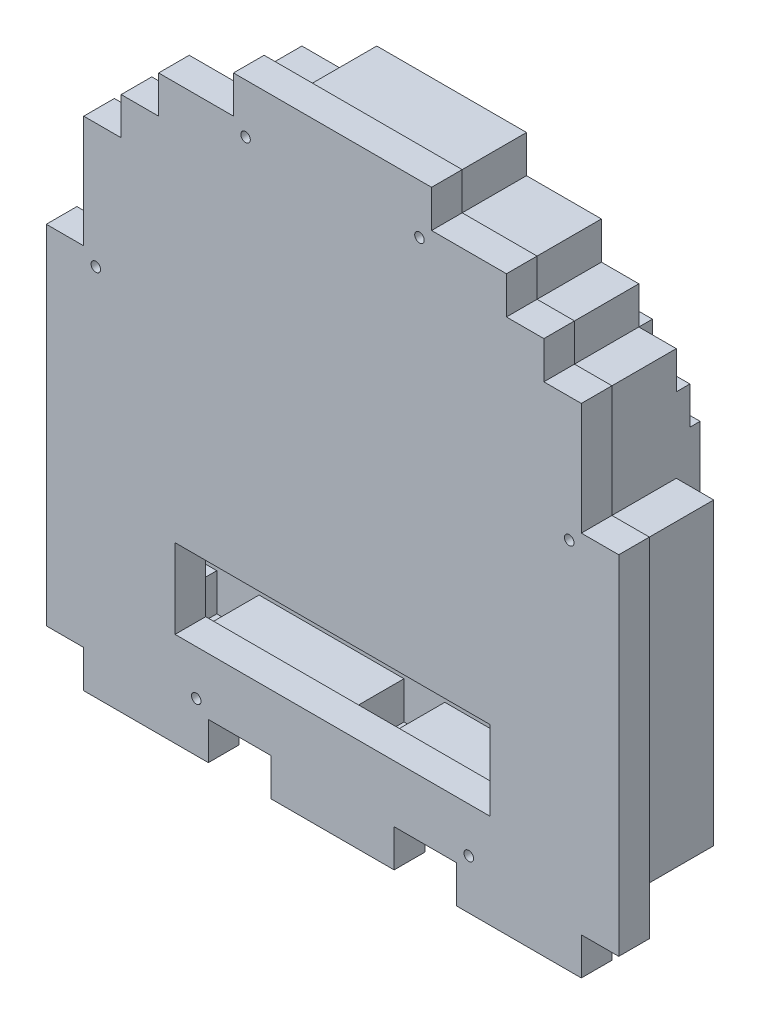
SolidWorks part; units mm, degrees
ref_plane "Alzado" through (0, 0, 0) normal (0, 0, 1) x (1, 0, 0)
ref_plane "Planta" through (0, 0, 0) normal (0, 1, 0) x (1, 0, 0)
ref_plane "Vista lateral" through (0, 0, 0) normal (1, 0, 0) x (0, 0, -1)
sketch "Croquis3" plane through (0, 0, 0) normal (0, 0, 1) x (1, 0, 0)
  line L0 (-78.9304, 27.6578) -> (-78.9304, -74.5422)
  line L1 (-78.9304, -74.5422) -> (-67.9304, -74.5422)
  line L2 (-67.9304, -74.5422) -> (-67.9304, -85.5422)
  line L3 (-67.9304, -85.5422) -> (-31.3168, -85.5422)
  line L4 (-31.3168, -85.5422) -> (-31.3168, -74.5422)
  line L5 (-31.3168, -74.5422) -> (-12.9304, -74.5422)
  line L6 (-12.9304, -74.5422) -> (-12.9304, -85.5422)
  line L7 (-12.9304, -85.5422) -> (23.2696, -85.5422)
  line L8 (23.2696, -85.5422) -> (23.2696, -74.5422)
  line L9 (23.2696, -74.5422) -> (41.656, -74.5422)
  line L10 (41.656, -74.5422) -> (41.656, -85.5422)
  line L11 (41.656, -85.5422) -> (78.2696, -85.5422)
  line L12 (78.2696, -85.5422) -> (78.2696, -74.5422)
  line L13 (78.2696, -74.5422) -> (89.2696, -74.5422)
  line L14 (89.2696, -74.5422) -> (89.2696, 27.6578)
  line L15 (89.2696, 27.6578) -> (78.2696, 27.6578)
  line L16 (78.2696, 27.6578) -> (78.2696, 60.6578)
  line L17 (78.2696, 60.6578) -> (67.2696, 60.6578)
  line L18 (67.2696, 60.6578) -> (67.2696, 71.6578)
  line L19 (67.2696, 71.6578) -> (56.2696, 71.6578)
  line L20 (56.2696, 71.6578) -> (56.2696, 82.6578)
  line L21 (56.2696, 82.6578) -> (34.2696, 82.6578)
  line L22 (34.2696, 82.6578) -> (34.2696, 93.6578)
  line L23 (34.2696, 93.6578) -> (-23.9304, 93.6578)
  line L24 (-23.9304, 93.6578) -> (-23.9304, 82.6578)
  line L25 (-23.9304, 82.6578) -> (-45.9304, 82.6578)
  line L26 (-45.9304, 82.6578) -> (-45.9304, 71.6578)
  line L27 (-45.9304, 71.6578) -> (-56.9304, 71.6578)
  line L28 (-56.9304, 71.6578) -> (-56.9304, 60.6578)
  line L29 (-56.9304, 60.6578) -> (-67.9304, 60.6578)
  line L30 (-67.9304, 60.6578) -> (-67.9304, 27.6578)
  line L31 (-67.9304, 27.6578) -> (-78.9304, 27.6578)
extrude "Saliente-Extruir1" add sketch "Croquis3" against normal blind 9
sketch "Croquis4" plane through (0, 0, -9) normal (0, 0, -1) x (-1, 0, 0)
  line L0 (-5.1696, 86.5578) -> (-5.1696, -112.2943) construction
  line L2 (-51.4317, -34.4538) -> (41.0925, -34.4538)
  line L3 (-51.4317, -34.4538) -> (-51.4317, -57.7913)
  line L4 (-51.4317, -57.7913) -> (41.0925, -57.7913)
  line L5 (41.0925, -34.4538) -> (41.0925, -57.7913)
  line L6 (-51.4317, -34.4538) -> (41.0925, -57.7913) construction
  line L7 (-51.4317, -57.7913) -> (41.0925, -34.4538) construction
  line L32 (-34.2696, 82.6578) -> (-27.1696, 75.5578) construction
  line L33 (-78.2696, 27.6578) -> (-71.1696, 20.5578) construction
  line L34 (-48.756, -67.4422) -> (-41.656, -74.5422) construction
  line L64 (71.8304, 20.5578) -> (60.8304, 20.5578)
  line L65 (60.8304, 20.5578) -> (60.8304, 53.5578)
  line L66 (60.8304, 53.5578) -> (49.8304, 53.5578)
  line L67 (49.8304, 53.5578) -> (49.8304, 64.5578)
  line L68 (49.8304, 64.5578) -> (38.8304, 64.5578)
  line L69 (38.8304, 64.5578) -> (38.8304, 75.5578)
  line L70 (38.8304, 75.5578) -> (16.8304, 75.5578)
  line L71 (16.8304, 75.5578) -> (16.8304, 86.5578)
  line L72 (16.8304, 86.5578) -> (-27.1696, 86.5578)
  line L73 (-27.1696, 86.5578) -> (-27.1696, 75.5578)
  line L74 (-27.1696, 75.5578) -> (-49.1696, 75.5578)
  line L75 (-49.1696, 75.5578) -> (-49.1696, 64.5578)
  line L76 (-49.1696, 64.5578) -> (-60.1696, 64.5578)
  line L77 (-60.1696, 64.5578) -> (-60.1696, 53.5578)
  line L78 (-60.1696, 53.5578) -> (-71.1696, 53.5578)
  line L79 (-71.1696, 53.5578) -> (-71.1696, 20.5578)
  line L80 (-71.1696, 20.5578) -> (-82.1696, 20.5578)
  line L81 (-82.1696, 20.5578) -> (-82.1696, -67.4422)
  line L82 (-82.1696, -67.4422) -> (-71.1696, -67.4422)
  line L83 (-71.1696, -67.4422) -> (-71.1696, -78.4422)
  line L84 (-71.1696, -78.4422) -> (-48.756, -78.4422)
  line L85 (-48.756, -78.4422) -> (-48.756, -67.4422)
  line L86 (-48.756, -67.4422) -> (-16.1696, -67.4422)
  line L87 (-16.1696, -67.4422) -> (-16.1696, -78.4422)
  line L88 (-16.1696, -78.4422) -> (5.8304, -78.4422)
  line L89 (5.8304, -78.4422) -> (5.8304, -67.4422)
  line L90 (5.8304, -67.4422) -> (38.4168, -67.4422)
  line L91 (38.4168, -67.4422) -> (38.4168, -78.4422)
  line L92 (38.4168, -78.4422) -> (60.8304, -78.4422)
  line L93 (60.8304, -78.4422) -> (60.8304, -67.4422)
  line L94 (60.8304, -67.4422) -> (71.8304, -67.4422)
  line L95 (71.8304, -67.4422) -> (71.8304, 20.5578)
  line L96 (71.8304, 20.5578) -> (60.8304, 20.5578)
  line L97 (60.8304, 20.5578) -> (60.8304, 53.5578)
  line L98 (60.8304, 53.5578) -> (49.8304, 53.5578)
  line L99 (49.8304, 53.5578) -> (49.8304, 64.5578)
  line L100 (49.8304, 64.5578) -> (38.8304, 64.5578)
  line L101 (38.8304, 64.5578) -> (38.8304, 75.5578)
  line L102 (38.8304, 75.5578) -> (16.8304, 75.5578)
  line L103 (16.8304, 75.5578) -> (16.8304, 86.5578)
  line L104 (16.8304, 86.5578) -> (-27.1696, 86.5578)
  line L105 (-27.1696, 86.5578) -> (-27.1696, 75.5578)
  line L106 (-27.1696, 75.5578) -> (-49.1696, 75.5578)
  line L107 (-49.1696, 75.5578) -> (-49.1696, 64.5578)
  line L108 (-49.1696, 64.5578) -> (-60.1696, 64.5578)
  line L109 (-60.1696, 64.5578) -> (-60.1696, 53.5578)
  line L110 (-60.1696, 53.5578) -> (-71.1696, 53.5578)
  line L111 (-71.1696, 53.5578) -> (-71.1696, 20.5578)
  line L112 (-71.1696, 20.5578) -> (-82.1696, 20.5578)
  line L113 (-82.1696, 20.5578) -> (-82.1696, -67.4422)
  line L114 (-82.1696, -67.4422) -> (-71.1696, -67.4422)
  line L115 (-71.1696, -67.4422) -> (-71.1696, -78.4422)
  line L116 (-71.1696, -78.4422) -> (-48.756, -78.4422)
  line L117 (-48.756, -78.4422) -> (-48.756, -67.4422)
  line L118 (-48.756, -67.4422) -> (-16.1696, -67.4422)
  line L119 (-16.1696, -67.4422) -> (-16.1696, -78.4422)
  line L120 (-16.1696, -78.4422) -> (5.8304, -78.4422)
  line L121 (5.8304, -78.4422) -> (5.8304, -67.4422)
  line L122 (5.8304, -67.4422) -> (38.4168, -67.4422)
  line L123 (38.4168, -67.4422) -> (38.4168, -78.4422)
  line L124 (38.4168, -78.4422) -> (60.8304, -78.4422)
  line L125 (60.8304, -78.4422) -> (60.8304, -67.4422)
  line L126 (60.8304, -67.4422) -> (71.8304, -67.4422)
  line L127 (71.8304, -67.4422) -> (71.8304, 20.5578)
  circle A0 centre (-30.7196, 79.1078) radius 1.4
  circle A1 centre (-74.7196, 24.1078) radius 1.4
  circle A2 centre (-45.206, -70.9922) radius 1.4
  circle A3 centre (34.8668, -70.9922) radius 1.4
  circle A4 centre (64.3804, 24.1078) radius 1.4
  circle A5 centre (20.3804, 79.1078) radius 1.4
  point P28 (-5.1696, -46.1225)
  dimension "D2" = 2.8
  dimension "D3" = 2.8
  dimension "D4" = 2.8
  dimension "D1" = 7.1
extrude "Cortar-Extruir1" cut sketch "Croquis4" against normal through all contours L5 L2 L3 L4 | A1 | A0 | A5 | A3 | A4 | A2
sketch "Croquis5" plane through (0, 0, -9) normal (0, 0, -1) x (-1, 0, 0)
  line L0 (-66.1696, 48.5578) -> (-66.1696, 15.5578)
  line L1 (-66.1696, 15.5578) -> (-77.1696, 15.5578)
  line L2 (-77.1696, 15.5578) -> (-77.1696, -62.4422)
  line L3 (-77.1696, -62.4422) -> (-66.1696, -62.4422)
  line L4 (-66.1696, -62.4422) -> (-66.1696, -73.4422)
  line L5 (-66.1696, -73.4422) -> (-53.756, -73.4422)
  line L6 (-53.756, -73.4422) -> (-53.756, -62.4422)
  line L7 (-53.756, -62.4422) -> (-11.1696, -62.4422)
  line L8 (-11.1696, -62.4422) -> (-11.1696, -73.4422)
  line L9 (-11.1696, -73.4422) -> (0.8304, -73.4422)
  line L10 (0.8304, -73.4422) -> (0.8304, -62.4422)
  line L11 (0.8304, -62.4422) -> (43.4168, -62.4422)
  line L12 (43.4168, -62.4422) -> (43.4168, -73.4422)
  line L13 (43.4168, -73.4422) -> (55.8304, -73.4422)
  line L14 (55.8304, -73.4422) -> (55.8304, -62.4422)
  line L15 (55.8304, -62.4422) -> (66.8304, -62.4422)
  line L16 (66.8304, -62.4422) -> (66.8304, 15.5578)
  line L17 (66.8304, 15.5578) -> (55.8304, 15.5578)
  line L18 (55.8304, 15.5578) -> (55.8304, 48.5578)
  line L19 (55.8304, 48.5578) -> (44.8304, 48.5578)
  line L20 (44.8304, 48.5578) -> (44.8304, 59.5578)
  line L21 (44.8304, 59.5578) -> (33.8304, 59.5578)
  line L22 (33.8304, 59.5578) -> (33.8304, 70.5578)
  line L23 (33.8304, 70.5578) -> (11.8304, 70.5578)
  line L24 (11.8304, 70.5578) -> (11.8304, 81.5578)
  line L25 (11.8304, 81.5578) -> (-22.1696, 81.5578)
  line L26 (-22.1696, 81.5578) -> (-22.1696, 70.5578)
  line L27 (-22.1696, 70.5578) -> (-44.1696, 70.5578)
  line L28 (-44.1696, 70.5578) -> (-44.1696, 59.5578)
  line L29 (-44.1696, 59.5578) -> (-55.1696, 59.5578)
  line L30 (-55.1696, 59.5578) -> (-55.1696, 48.5578)
  line L31 (-55.1696, 48.5578) -> (-66.1696, 48.5578)
  line L64 (71.8304, 20.5578) -> (60.8304, 20.5578)
  line L65 (60.8304, 20.5578) -> (60.8304, 53.5578)
  line L66 (60.8304, 53.5578) -> (49.8304, 53.5578)
  line L67 (49.8304, 53.5578) -> (49.8304, 64.5578)
  line L68 (49.8304, 64.5578) -> (38.8304, 64.5578)
  line L69 (38.8304, 64.5578) -> (38.8304, 75.5578)
  line L70 (38.8304, 75.5578) -> (16.8304, 75.5578)
  line L71 (16.8304, 75.5578) -> (16.8304, 86.5578)
  line L72 (16.8304, 86.5578) -> (-27.1696, 86.5578)
  line L73 (-27.1696, 86.5578) -> (-27.1696, 75.5578)
  line L74 (-27.1696, 75.5578) -> (-49.1696, 75.5578)
  line L75 (-49.1696, 75.5578) -> (-49.1696, 64.5578)
  line L76 (-49.1696, 64.5578) -> (-60.1696, 64.5578)
  line L77 (-60.1696, 64.5578) -> (-60.1696, 53.5578)
  line L78 (-60.1696, 53.5578) -> (-71.1696, 53.5578)
  line L79 (-71.1696, 53.5578) -> (-71.1696, 20.5578)
  line L80 (-71.1696, 20.5578) -> (-82.1696, 20.5578)
  line L81 (-82.1696, 20.5578) -> (-82.1696, -67.4422)
  line L82 (-82.1696, -67.4422) -> (-71.1696, -67.4422)
  line L83 (-71.1696, -67.4422) -> (-71.1696, -78.4422)
  line L84 (-71.1696, -78.4422) -> (-48.756, -78.4422)
  line L85 (-48.756, -78.4422) -> (-48.756, -67.4422)
  line L86 (-48.756, -67.4422) -> (-16.1696, -67.4422)
  line L87 (-16.1696, -67.4422) -> (-16.1696, -78.4422)
  line L88 (-16.1696, -78.4422) -> (5.8304, -78.4422)
  line L89 (5.8304, -78.4422) -> (5.8304, -67.4422)
  line L90 (5.8304, -67.4422) -> (38.4168, -67.4422)
  line L91 (38.4168, -67.4422) -> (38.4168, -78.4422)
  line L92 (38.4168, -78.4422) -> (60.8304, -78.4422)
  line L93 (60.8304, -78.4422) -> (60.8304, -67.4422)
  line L94 (60.8304, -67.4422) -> (71.8304, -67.4422)
  line L95 (71.8304, -67.4422) -> (71.8304, 20.5578)
  line L96 (71.8304, 20.5578) -> (60.8304, 20.5578)
  line L97 (60.8304, 20.5578) -> (60.8304, 53.5578)
  line L98 (60.8304, 53.5578) -> (49.8304, 53.5578)
  line L99 (49.8304, 53.5578) -> (49.8304, 64.5578)
  line L100 (49.8304, 64.5578) -> (38.8304, 64.5578)
  line L101 (38.8304, 64.5578) -> (38.8304, 75.5578)
  line L102 (38.8304, 75.5578) -> (16.8304, 75.5578)
  line L103 (16.8304, 75.5578) -> (16.8304, 86.5578)
  line L104 (16.8304, 86.5578) -> (-27.1696, 86.5578)
  line L105 (-27.1696, 86.5578) -> (-27.1696, 75.5578)
  line L106 (-27.1696, 75.5578) -> (-49.1696, 75.5578)
  line L107 (-49.1696, 75.5578) -> (-49.1696, 64.5578)
  line L108 (-49.1696, 64.5578) -> (-60.1696, 64.5578)
  line L109 (-60.1696, 64.5578) -> (-60.1696, 53.5578)
  line L110 (-60.1696, 53.5578) -> (-71.1696, 53.5578)
  line L111 (-71.1696, 53.5578) -> (-71.1696, 20.5578)
  line L112 (-71.1696, 20.5578) -> (-82.1696, 20.5578)
  line L113 (-82.1696, 20.5578) -> (-82.1696, -67.4422)
  line L114 (-82.1696, -67.4422) -> (-71.1696, -67.4422)
  line L115 (-71.1696, -67.4422) -> (-71.1696, -78.4422)
  line L116 (-71.1696, -78.4422) -> (-48.756, -78.4422)
  line L117 (-48.756, -78.4422) -> (-48.756, -67.4422)
  line L118 (-48.756, -67.4422) -> (-16.1696, -67.4422)
  line L119 (-16.1696, -67.4422) -> (-16.1696, -78.4422)
  line L120 (-16.1696, -78.4422) -> (5.8304, -78.4422)
  line L121 (5.8304, -78.4422) -> (5.8304, -67.4422)
  line L122 (5.8304, -67.4422) -> (38.4168, -67.4422)
  line L123 (38.4168, -67.4422) -> (38.4168, -78.4422)
  line L124 (38.4168, -78.4422) -> (60.8304, -78.4422)
  line L125 (60.8304, -78.4422) -> (60.8304, -67.4422)
  line L126 (60.8304, -67.4422) -> (71.8304, -67.4422)
  line L127 (71.8304, -67.4422) -> (71.8304, 20.5578)
  dimension "D1" = 7.1
  dimension "D2" = 5
extrude "Saliente-Extruir2" add sketch "Croquis5" along normal blind 18
sketch "Croquis7" plane through (0, 0, -27) normal (0, 0, -1) x (-1, 0, 0)
  line L32 (71.8304, -67.4422) -> (71.8304, 20.5578)
  line L33 (71.8304, 20.5578) -> (60.8304, 20.5578)
  line L34 (60.8304, 20.5578) -> (60.8304, 53.5578)
  line L35 (60.8304, 53.5578) -> (49.8304, 53.5578)
  line L36 (49.8304, 53.5578) -> (49.8304, 64.5578)
  line L37 (49.8304, 64.5578) -> (38.8304, 64.5578)
  line L38 (38.8304, 64.5578) -> (38.8304, 75.5578)
  line L39 (38.8304, 75.5578) -> (16.8304, 75.5578)
  line L40 (16.8304, 75.5578) -> (16.8304, 86.5578)
  line L41 (16.8304, 86.5578) -> (-27.1696, 86.5578)
  line L42 (-27.1696, 86.5578) -> (-27.1696, 75.5578)
  line L43 (-27.1696, 75.5578) -> (-49.1696, 75.5578)
  line L44 (-49.1696, 75.5578) -> (-49.1696, 64.5578)
  line L45 (-49.1696, 64.5578) -> (-60.1696, 64.5578)
  line L46 (-60.1696, 64.5578) -> (-60.1696, 53.5578)
  line L47 (-60.1696, 53.5578) -> (-71.1696, 53.5578)
  line L48 (-71.1696, 53.5578) -> (-71.1696, 20.5578)
  line L49 (-71.1696, 20.5578) -> (-82.1696, 20.5578)
  line L50 (-82.1696, 20.5578) -> (-82.1696, -67.4422)
  line L51 (-82.1696, -67.4422) -> (-71.1696, -67.4422)
  line L52 (-71.1696, -67.4422) -> (-71.1696, -78.4422)
  line L53 (-71.1696, -78.4422) -> (-48.756, -78.4422)
  line L54 (-48.756, -78.4422) -> (-48.756, -67.4422)
  line L55 (-48.756, -67.4422) -> (-16.1696, -67.4422)
  line L56 (-16.1696, -67.4422) -> (-16.1696, -78.4422)
  line L57 (-16.1696, -78.4422) -> (5.8304, -78.4422)
  line L58 (5.8304, -78.4422) -> (5.8304, -67.4422)
  line L59 (5.8304, -67.4422) -> (38.4168, -67.4422)
  line L60 (38.4168, -67.4422) -> (38.4168, -78.4422)
  line L61 (38.4168, -78.4422) -> (60.8304, -78.4422)
  line L62 (60.8304, -78.4422) -> (60.8304, -67.4422)
  line L63 (60.8304, -67.4422) -> (71.8304, -67.4422)
  line L64 (71.8304, -67.4422) -> (71.8304, 20.5578)
  line L65 (71.8304, 20.5578) -> (60.8304, 20.5578)
  line L66 (60.8304, 20.5578) -> (60.8304, 53.5578)
  line L67 (60.8304, 53.5578) -> (49.8304, 53.5578)
  line L68 (49.8304, 53.5578) -> (49.8304, 64.5578)
  line L69 (49.8304, 64.5578) -> (38.8304, 64.5578)
  line L70 (38.8304, 64.5578) -> (38.8304, 75.5578)
  line L71 (38.8304, 75.5578) -> (16.8304, 75.5578)
  line L72 (16.8304, 75.5578) -> (16.8304, 86.5578)
  line L73 (16.8304, 86.5578) -> (-27.1696, 86.5578)
  line L74 (-27.1696, 86.5578) -> (-27.1696, 75.5578)
  line L75 (-27.1696, 75.5578) -> (-49.1696, 75.5578)
  line L76 (-49.1696, 75.5578) -> (-49.1696, 64.5578)
  line L77 (-49.1696, 64.5578) -> (-60.1696, 64.5578)
  line L78 (-60.1696, 64.5578) -> (-60.1696, 53.5578)
  line L79 (-60.1696, 53.5578) -> (-71.1696, 53.5578)
  line L80 (-71.1696, 53.5578) -> (-71.1696, 20.5578)
  line L81 (-71.1696, 20.5578) -> (-82.1696, 20.5578)
  line L82 (-82.1696, 20.5578) -> (-82.1696, -67.4422)
  line L83 (-82.1696, -67.4422) -> (-71.1696, -67.4422)
  line L84 (-71.1696, -67.4422) -> (-71.1696, -78.4422)
  line L85 (-71.1696, -78.4422) -> (-48.756, -78.4422)
  line L86 (-48.756, -78.4422) -> (-48.756, -67.4422)
  line L87 (-48.756, -67.4422) -> (-16.1696, -67.4422)
  line L88 (-16.1696, -67.4422) -> (-16.1696, -78.4422)
  line L89 (-16.1696, -78.4422) -> (5.8304, -78.4422)
  line L90 (5.8304, -78.4422) -> (5.8304, -67.4422)
  line L91 (5.8304, -67.4422) -> (38.4168, -67.4422)
  line L92 (38.4168, -67.4422) -> (38.4168, -78.4422)
  line L93 (38.4168, -78.4422) -> (60.8304, -78.4422)
  line L94 (60.8304, -78.4422) -> (60.8304, -67.4422)
  line L95 (60.8304, -67.4422) -> (71.8304, -67.4422)
  dimension "D1" = 0
extrude "Saliente-Extruir3" add sketch "Croquis7" along normal blind 8
sketch "Croquis8" plane through (0, 0, -35) normal (0, 0, -1) x (-1, 0, 0)
  line L0 (-71.1696, 20.5578) -> (-71.1696, 9.5578)
  line L1 (-71.1696, 9.5578) -> (-60.1696, 9.5578)
  line L2 (-60.1696, 9.5578) -> (-60.1696, -1.4422)
  line L3 (-60.1696, -1.4422) -> (-38.1696, -1.4422)
  line L4 (-71.1696, 42.5578) -> (-60.1696, 42.5578)
  line L5 (-71.1696, 53.5578) -> (-71.1696, 20.5578) construction
  line L6 (-60.1696, 42.5578) -> (-60.1696, 53.5578)
  line L7 (-60.1696, 53.5578) -> (-38.1696, 53.5578)
  line L8 (-49.1696, 53.5578) -> (-49.1696, -11.1557) construction
  line L9 (-71.1696, 42.5578) -> (-71.1696, 20.5578)
  line L10 (-38.1696, 42.5578) -> (-38.1696, 53.5578)
  line L11 (-27.1696, 42.5578) -> (-38.1696, 42.5578)
  line L12 (-38.1696, 9.5578) -> (-38.1696, -1.4422)
  line L13 (-27.1696, 9.5578) -> (-38.1696, 9.5578)
  line L14 (-27.1696, 20.5578) -> (-27.1696, 9.5578)
  line L15 (-27.1696, 42.5578) -> (-27.1696, 20.5578)
  line L16 (-16.1696, 86.5578) -> (-16.1696, -28.7463) construction
  line L17 (16.8304, 86.5578) -> (-27.1696, 86.5578) construction
  line L18 (38.8304, 20.5578) -> (38.8304, 9.5578)
  line L19 (38.8304, 42.5578) -> (38.8304, 20.5578)
  line L20 (-5.1696, 20.5578) -> (-5.1696, 9.5578)
  line L21 (-5.1696, 42.5578) -> (-5.1696, 20.5578)
  line L22 (16.8304, 53.5578) -> (16.8304, -11.1557) construction
  line L23 (-5.1696, 9.5578) -> (5.8304, 9.5578)
  line L24 (5.8304, 9.5578) -> (5.8304, -1.4422)
  line L25 (-5.1696, 42.5578) -> (5.8304, 42.5578)
  line L26 (5.8304, 42.5578) -> (5.8304, 53.5578)
  line L27 (27.8304, 53.5578) -> (5.8304, 53.5578)
  line L28 (27.8304, 42.5578) -> (27.8304, 53.5578)
  line L29 (38.8304, 42.5578) -> (27.8304, 42.5578)
  line L30 (27.8304, -1.4422) -> (5.8304, -1.4422)
  line L31 (27.8304, 9.5578) -> (27.8304, -1.4422)
  line L32 (38.8304, 9.5578) -> (27.8304, 9.5578)
  dimension "D1" = 11
  dimension "D2" = 11
  dimension "D3" = 11
  dimension "D4" = 22
  dimension "D5" = 22
  dimension "D6" = 11
extrude "Saliente-Extruir4" add sketch "Croquis8" along normal blind 4
sketch "Croquis9" plane through (0, 0, -39) normal (0, 0, -1) x (-1, 0, 0)
  line L0 (-71.1696, 31.5578) -> (-49.1696, 31.5578)
  line L1 (-71.1696, 42.5578) -> (-71.1696, 9.5578) construction
  line L2 (-49.1696, 31.5578) -> (-49.1696, 9.5578)
  line L3 (-49.1696, 9.5578) -> (-71.1696, 9.5578)
  line L4 (-5.1696, 9.5578) -> (16.8304, 9.5578)
  line L5 (-5.1696, 9.5578) -> (5.8304, 9.5578) construction
  line L6 (-5.1696, 42.5578) -> (-5.1696, 9.5578) construction
  line L7 (-5.1696, 31.5578) -> (16.8304, 31.5578)
  line L8 (16.8304, 31.5578) -> (16.8304, 9.5578)
  line L9 (-5.1696, 31.5578) -> (-5.1696, 9.5578)
  line L10 (-71.1696, 31.5578) -> (-71.1696, 9.5578)
  dimension "D1" = 22
  dimension "D2" = 22
  dimension "D3" = 22
extrude "Saliente-Extruir5" add sketch "Croquis9" along normal blind 3
